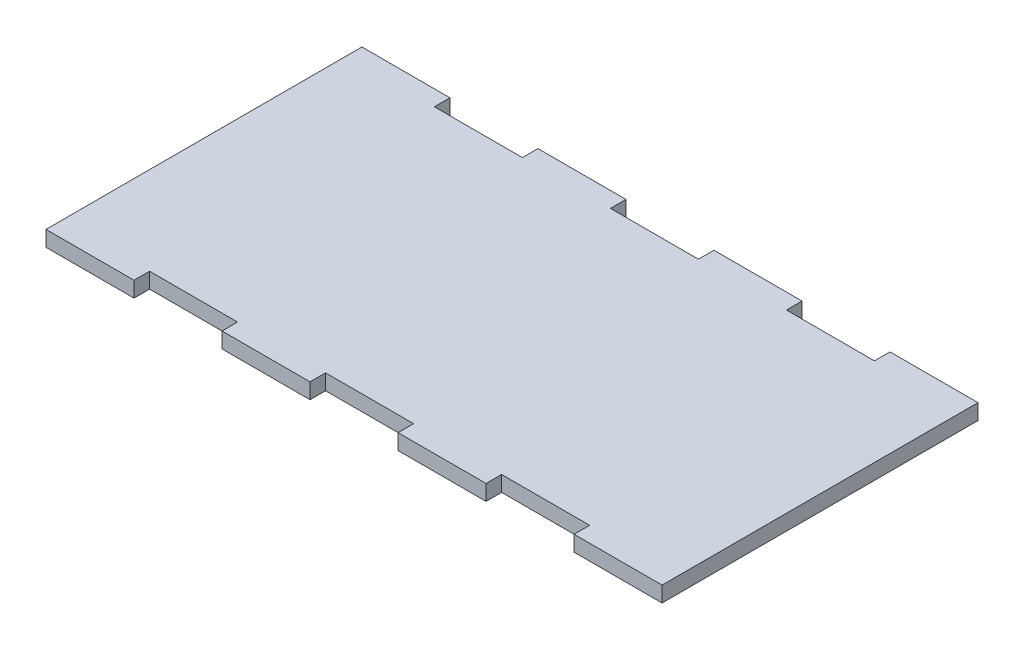
SolidWorks part; units mm, degrees
ref_plane "Front Plane" through (0, 0, 0) normal (0, 0, 1) x (1, 0, 0)
ref_plane "Top Plane" through (0, 0, 0) normal (0, 1, 0) x (1, 0, 0)
ref_plane "Right Plane" through (0, 0, 0) normal (1, 0, 0) x (0, 0, -1)
sketch "Sketch1" plane through (0, 0, 0) normal (0, 1, 0) x (1, 0, 0)
  line L1 (49.53, -25.4) -> (-49.53, -25.4)
  line L2 (49.53, -25.4) -> (49.53, 25.4)
  line L3 (49.53, 25.4) -> (-49.53, 25.4)
  line L4 (-49.53, -25.4) -> (-49.53, 25.4)
  line L5 (49.53, -25.4) -> (-49.53, 25.4) construction
  line L6 (49.53, 25.4) -> (-49.53, -25.4) construction
  point P0 (0, 0)
  dimension "D1" = 99.06
  dimension "D2" = 50.8
extrude "Boss-Extrude1" add sketch "Sketch1" along normal blind 2.5
sketch "Sketch2" plane through (0, 2.5, 0) normal (0, 1, 0) x (1, 0, 0)
  line L0 (-49.53, 22.9) -> (49.53, 22.9) construction
  line L1 (-49.53, 25.4) -> (-49.53, -25.4) construction
  line L2 (49.53, -25.4) -> (49.53, 25.4) construction
  line L3 (-49.53, -22.9) -> (49.53, -22.9) construction
  line L4 (49.53, 25.4) -> (-49.53, 25.4) construction
  line L5 (-49.53, -25.4) -> (49.53, -25.4) construction
  line L6 (-49.53, 25.4) -> (-35.3786, 25.4) construction
  line L7 (-35.3786, 25.4) -> (-21.2271, 25.4)
  line L8 (-35.3786, 25.4) -> (-35.3786, 22.9)
  line L9 (-35.3786, 22.9) -> (-21.2271, 22.9)
  line L10 (-21.2271, 25.4) -> (-21.2271, 22.9)
  line L11 (-7.0757, 25.4) -> (7.0757, 25.4)
  line L12 (-7.0757, 25.4) -> (-7.0757, 22.9)
  line L13 (-7.0757, 22.9) -> (7.0757, 22.9)
  line L14 (7.0757, 25.4) -> (7.0757, 22.9)
  line L15 (21.2271, 25.4) -> (35.3786, 25.4)
  line L16 (21.2271, 25.4) -> (21.2271, 22.9)
  line L17 (21.2271, 22.9) -> (35.3786, 22.9)
  line L18 (35.3786, 25.4) -> (35.3786, 22.9)
  line L19 (-21.2271, 25.4) -> (-7.0757, 25.4) construction
  line L20 (7.0757, 25.4) -> (21.2271, 25.4) construction
  line L21 (35.3786, 25.4) -> (49.53, 25.4) construction
  line L22 (-49.53, -25.4) -> (-35.3786, -25.4) construction
  line L23 (-35.3786, -22.9) -> (-21.2271, -22.9)
  line L24 (-35.3786, -22.9) -> (-35.3786, -25.4)
  line L25 (-35.3786, -25.4) -> (-21.2271, -25.4)
  line L26 (-21.2271, -22.9) -> (-21.2271, -25.4)
  line L27 (-7.0757, -22.9) -> (7.0757, -22.9)
  line L28 (-7.0757, -22.9) -> (-7.0757, -25.4)
  line L29 (-7.0757, -25.4) -> (7.0757, -25.4)
  line L30 (7.0757, -22.9) -> (7.0757, -25.4)
  line L31 (21.2271, -22.9) -> (35.3786, -22.9)
  line L32 (21.2271, -22.9) -> (21.2271, -25.4)
  line L33 (21.2271, -25.4) -> (35.3786, -25.4)
  line L34 (35.3786, -22.9) -> (35.3786, -25.4)
  line L35 (-21.2271, -25.4) -> (-7.0757, -25.4) construction
  line L36 (7.0757, -25.4) -> (21.2271, -25.4) construction
  line L37 (35.3786, -25.4) -> (49.53, -25.4) construction
  dimension "D1" = 2.5
  dimension "D2" = 2.5
extrude "Cut-Extrude1" cut sketch "Sketch2" against normal blind 2.54
